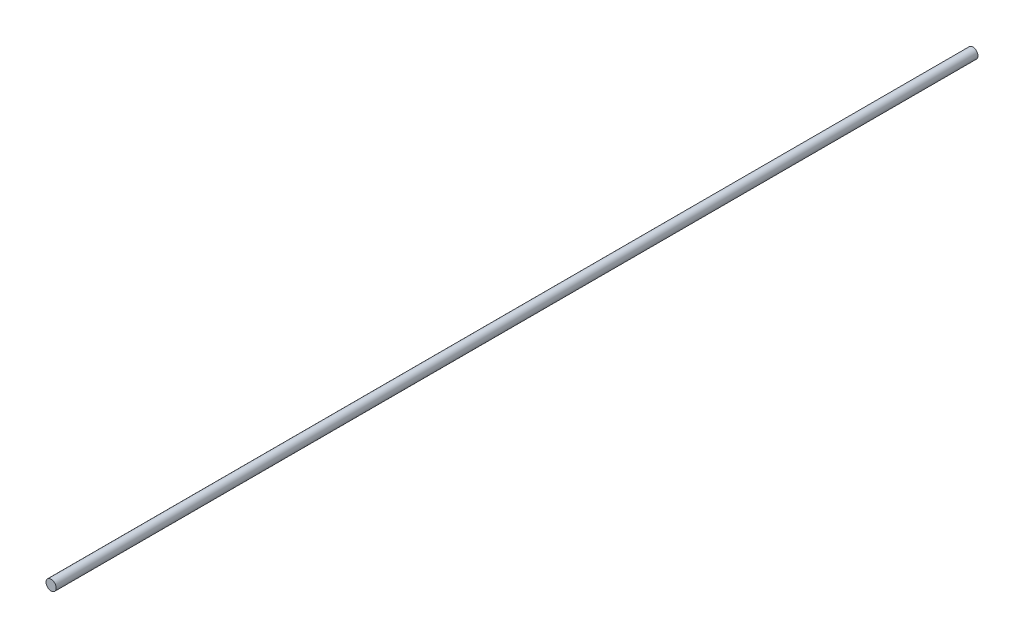
SolidWorks part; units mm, degrees
ref_plane "Front Plane" through (0, 0, 0) normal (0, 0, 1) x (1, 0, 0)
ref_plane "Top Plane" through (0, 0, 0) normal (0, 1, 0) x (1, 0, 0)
ref_plane "Right Plane" through (0, 0, 0) normal (1, 0, 0) x (0, 0, -1)
sketch "Sketch1" plane through (0, 0, 0) normal (0, 0, 1) x (1, 0, 0)
  circle A0 centre (0, 0) radius 4
  dimension "D1" = 8
extrude "Boss-Extrude1" add sketch "Sketch1" along normal blind 721
